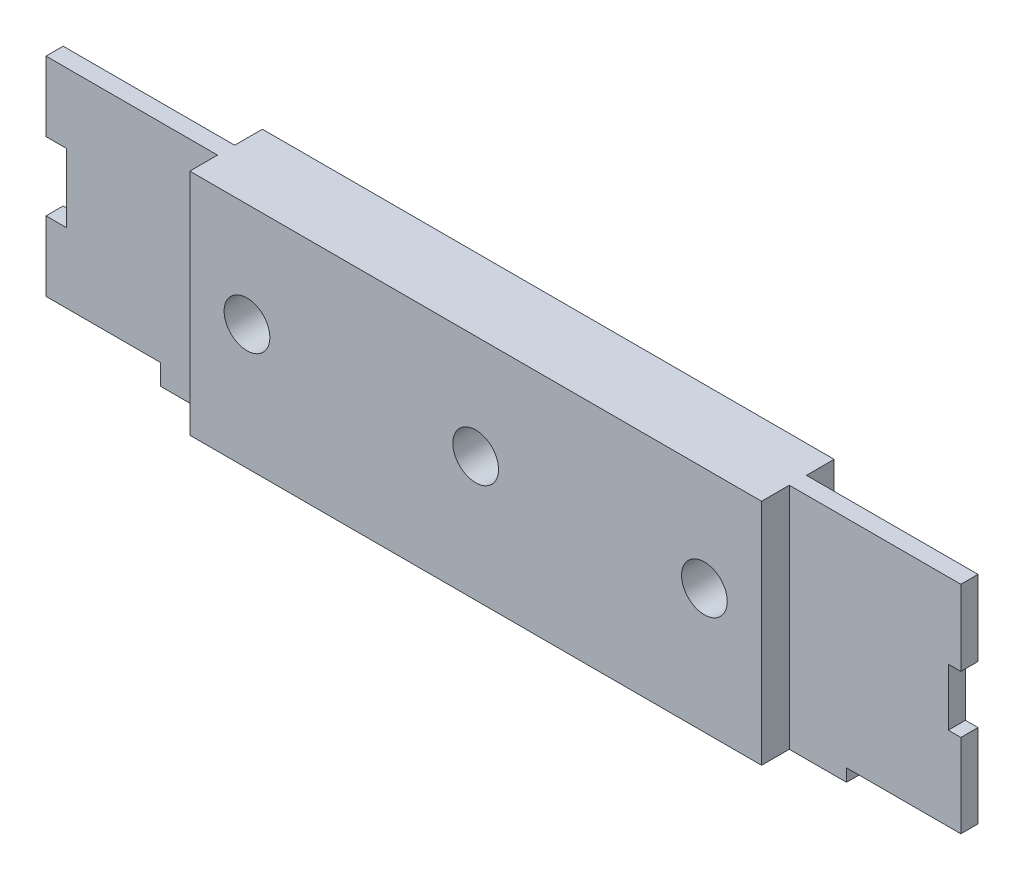
SolidWorks part; units mm, degrees
ref_plane "Alzado" through (0, 0, 0) normal (0, 0, 1) x (1, 0, 0)
ref_plane "Planta" through (0, 0, 0) normal (0, 1, 0) x (1, 0, 0)
ref_plane "Vista lateral" through (0, 0, 0) normal (1, 0, 0) x (0, 0, -1)
sketch "Croquis1" plane through (0, 0, 0) normal (0, 0, 1) x (1, 0, 0)
  line L0 (-40, 9.1) -> (40, 9.1)
  line L1 (40, 9.1) -> (40, 2.5)
  line L2 (40, 2.5) -> (38.9, 2.5)
  line L3 (38.9, 2.5) -> (38.9, -2.5)
  line L4 (38.9, -2.5) -> (40, -2.5)
  line L5 (40, -2.5) -> (40, -9.8)
  line L6 (40, -9.8) -> (30, -9.8)
  line L7 (30, -9.8) -> (30, -10.9)
  line L8 (30, -10.9) -> (-30, -10.9)
  line L9 (-30, -10.9) -> (-30, -9.1)
  line L10 (-30, -9.1) -> (-40, -9.1)
  line L11 (-40, -9.1) -> (-40, -3)
  line L12 (-40, -3) -> (-38.2, -3)
  line L13 (-38.2, -3) -> (-38.2, 3)
  line L14 (-38.2, 3) -> (-40, 3)
  line L15 (-40, 3) -> (-40, 9.1)
  line L16 (38.9, 0) -> (-38.2, 0) construction
  circle A0 centre (20, 0) radius 2
  circle A1 centre (0, 0) radius 2
  circle A2 centre (-20, 0) radius 2
  point P16 (-38.2, 0)
  point P18 (38.9, 0)
  point P19 (0, 9.1)
  dimension "D9" = 4
  dimension "D10" = 20
  dimension "D11" = 20
  dimension "D12" = 20
  dimension "D1" = 80
  dimension "D2" = 10
  dimension "D3" = 10
  dimension "D4" = 20
  dimension "D5" = 6
  dimension "D6" = 5
  dimension "D7" = 1.8
  dimension "D8" = 1.1
extrude "Saliente-Extruir1" add sketch "Croquis1" along normal mid plane 1.5
sketch "Croquis2" plane through (0, 0, 0) normal (0, 0, 1) x (1, 0, 0)
  line L0 (40, 9.1) -> (-40, 9.1) construction
  line L1 (-25, 9.1) -> (25, 9.1)
  line L2 (-25, 9.1) -> (-25, -10.9)
  line L3 (-25, -10.9) -> (25, -10.9)
  line L4 (25, 9.1) -> (25, -10.9)
  line L5 (-30, -10.9) -> (30, -10.9) construction
  line L6 (-40, 9.1) -> (-40, 3) construction
  line L7 (40, 2.5) -> (40, 9.1) construction
  circle A0 centre (-20, 0) radius 2
  circle A1 centre (0, 0) radius 2
  circle A2 centre (20, 0) radius 2
  dimension "D1" = 15
  dimension "D2" = 15
extrude "Saliente-Extruir2" add sketch "Croquis2" along normal mid plane 6.35
